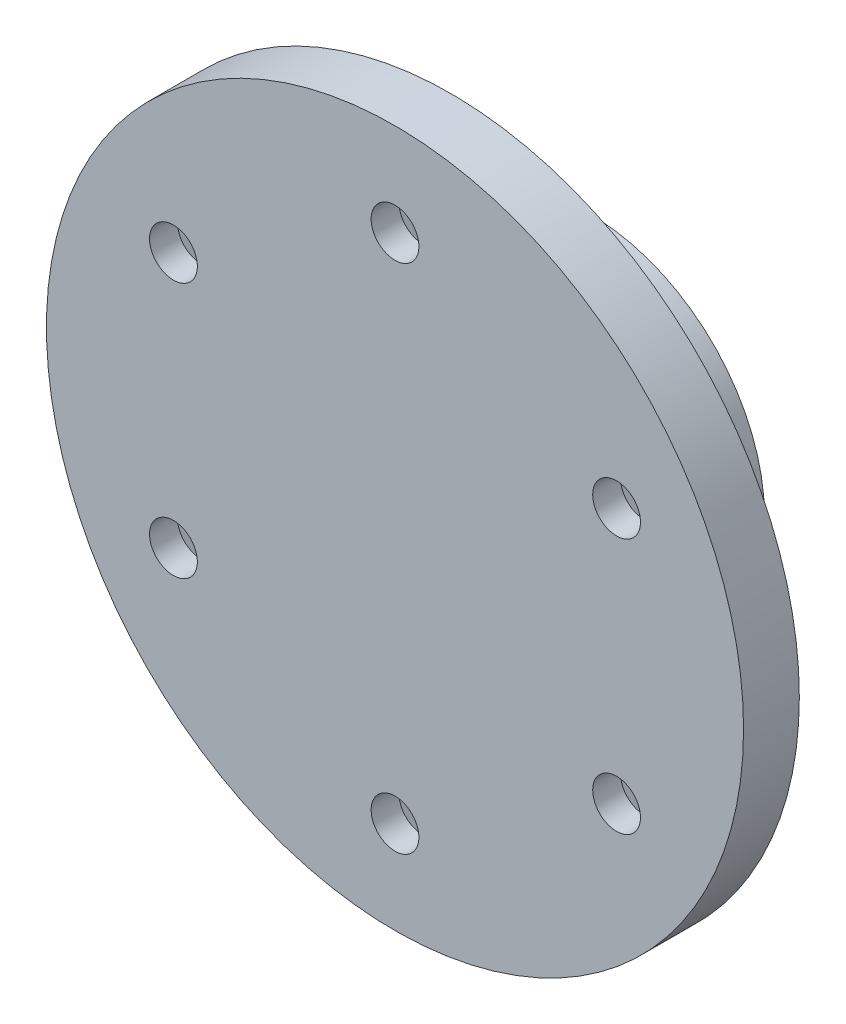
SolidWorks part; units mm, degrees
ref_plane "Front Plane" through (0, 0, 0) normal (0, 0, 1) x (1, 0, 0)
ref_plane "Top Plane" through (0, 0, 0) normal (0, 1, 0) x (1, 0, 0)
ref_plane "Right Plane" through (0, 0, 0) normal (1, 0, 0) x (0, 0, -1)
sketch "Sketch1" plane through (0, 0, 0) normal (0, 0, 1) x (1, 0, 0)
  circle A0 centre (0, 0) radius 25
  dimension "D1" = 50
extrude "Boss-Extrude1" add sketch "Sketch1" along normal blind 4
sketch "Sketch2" plane through (0, 0, 0) normal (0, 0, -1) x (-1, 0, 0)
  line L0 (0, 0) -> (0, 18.35) construction
  circle A0 centre (0, 18.35) radius 1.7136
  circle A1 centre (15.8916, 9.175) radius 1.7136
  circle A2 centre (15.8916, -9.175) radius 1.7136
  circle A3 centre (0, -18.35) radius 1.7136
  circle A4 centre (-15.8916, -9.175) radius 1.7136
  circle A5 centre (-15.8916, 9.175) radius 1.7136
  point P17 (0, 0)
  dimension "D1" = 18.35
  dimension "D2" = 6
extrude "Cut-Extrude1" cut sketch "Sketch2" against normal blind 4
sketch "Sketch3" plane through (0, 0, 0) normal (0, 0, -1) x (-1, 0, 0)
  line L0 (13.8708, 5.675) -> (17.9123, 5.675)
  line L1 (4.0415, 18.35) -> (2.0207, 21.85)
  line L2 (2.0207, 21.85) -> (-2.0207, 21.85)
  line L3 (-2.0207, 21.85) -> (-4.0415, 18.35)
  line L4 (-4.0415, 18.35) -> (-2.0207, 14.85)
  line L5 (-2.0207, 14.85) -> (2.0207, 14.85)
  line L6 (2.0207, 14.85) -> (4.0415, 18.35)
  line L7 (17.9123, 5.675) -> (19.933, 9.175)
  line L8 (19.933, 9.175) -> (17.9123, 12.675)
  line L9 (17.9123, 12.675) -> (13.8708, 12.675)
  line L10 (13.8708, 12.675) -> (11.8501, 9.175)
  line L11 (11.8501, 9.175) -> (13.8708, 5.675)
  line L12 (11.8501, -9.175) -> (13.8708, -12.675)
  line L13 (13.8708, -12.675) -> (17.9123, -12.675)
  line L14 (17.9123, -12.675) -> (19.933, -9.175)
  line L15 (19.933, -9.175) -> (17.9123, -5.675)
  line L16 (17.9123, -5.675) -> (13.8708, -5.675)
  line L17 (13.8708, -5.675) -> (11.8501, -9.175)
  line L18 (-2.0207, -14.85) -> (-4.0415, -18.35)
  line L19 (-4.0415, -18.35) -> (-2.0207, -21.85)
  line L20 (-2.0207, -21.85) -> (2.0207, -21.85)
  line L21 (2.0207, -21.85) -> (4.0415, -18.35)
  line L22 (4.0415, -18.35) -> (2.0207, -14.85)
  line L23 (2.0207, -14.85) -> (-2.0207, -14.85)
  line L24 (-13.8708, -5.675) -> (-17.9123, -5.675)
  line L25 (-17.9123, -5.675) -> (-19.933, -9.175)
  line L26 (-19.933, -9.175) -> (-17.9123, -12.675)
  line L27 (-17.9123, -12.675) -> (-13.8708, -12.675)
  line L28 (-13.8708, -12.675) -> (-11.8501, -9.175)
  line L29 (-11.8501, -9.175) -> (-13.8708, -5.675)
  line L30 (-11.8501, 9.175) -> (-13.8708, 12.675)
  line L31 (-13.8708, 12.675) -> (-17.9123, 12.675)
  line L32 (-17.9123, 12.675) -> (-19.933, 9.175)
  line L33 (-19.933, 9.175) -> (-17.9123, 5.675)
  line L34 (-17.9123, 5.675) -> (-13.8708, 5.675)
  line L35 (-13.8708, 5.675) -> (-11.8501, 9.175)
  circle A0 centre (0, 18.35) radius 3.5 construction
  point P42 (0, 0)
  dimension "D1" = 7
  dimension "D2" = 6
extrude "Cut-Extrude2" cut sketch "Sketch3" against normal blind 2
sketch "Sketch4" plane through (0, 0, 0) normal (0, 0, -1) x (-1, 0, 0)
  line L0 (0, 0) -> (0, 1) construction
  circle A1 centre (0, 1) radius 3
  circle A2 centre (0, 0) radius 12.5
  dimension "D1" = 6
  dimension "D3" = 25
  dimension "D2" = 1
extrude "Boss-Extrude2" add sketch "Sketch4" along normal blind 10
ref_plane "Plane1" through (0, 12.5, 0) normal (0, 1, 0) x (1, 0, 0)
sketch "Sketch5" plane through (0, 12.5, 0) normal (0, 1, 0) x (1, 0, 0)
  circle A0 centre (0, 5) radius 1.6
  point P5 (0.3712, -0.0662)
  dimension "D1" = 3.2
  dimension "D2" = 5
  dimension "D3" = 12.5
extrude "Cut-Extrude3" cut sketch "Sketch5" against normal blind 12.5
sketch "Sketch6" plane through (0, 12.5, 0) normal (0, 1, 0) x (1, 0, 0)
  circle A0 centre (0, 5) radius 3.1
  dimension "D1" = 6.2
extrude "Cut-Extrude4" cut sketch "Sketch6" against normal blind 6
ref_plane "Plane2" through (0, 1.5, 0) normal (0, 1, 0) x (1, 0, 0)
sketch "Sketch7" plane through (0, 1.5, 0) normal (0, 1, 0) x (1, 0, 0)
  line L1 (2.1743, 7.9) -> (-12.5, 7.9)
  line L3 (2.1743, 2.1) -> (-12.5, 2.1)
  line L4 (-12.5, 7.9) -> (-12.5, 2.1)
  line L5 (3, 10) -> (-3, 10) construction
  line L15 (2.1743, 7.9) -> (3.8486, 5)
  line L16 (3.8486, 5) -> (2.1743, 2.1)
  dimension "D5" = 16.3486
  dimension "D1" = 14.6743
  dimension "D2" = 5.8
  dimension "D3" = 2.1
  dimension "D4" = 14.6743
extrude "Cut-Extrude5" cut sketch "Sketch7" along normal blind 3
sketch "Sketch8" plane through (0, 0, 0) normal (0, 0, -1) x (-1, 0, 0)
  circle A0 centre (0, 1) radius 3 construction
  circle A1 centre (0, 0) radius 25 construction
  point P0 (0, -2)
  point P5 (0, 25)
fillet "Fillet1" radius 1.5 1 edges at (12.5, 0, 0)
equation "\"mm\"=1.5"
